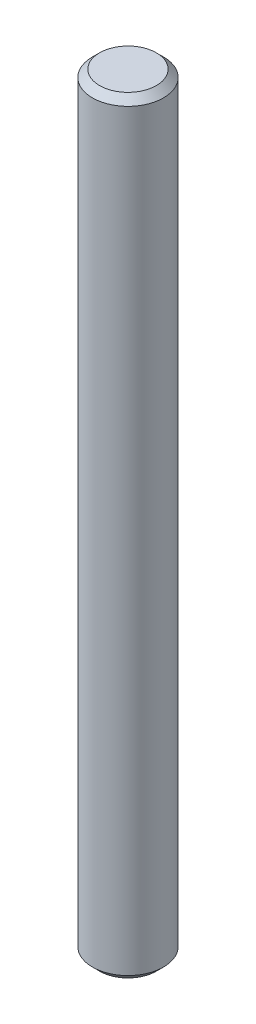
SolidWorks part; units mm, degrees
ref_plane "前视基准面" through (0, 0, 0) normal (0, 0, 1) x (1, 0, 0)
ref_plane "上视基准面" through (0, 0, 0) normal (0, 1, 0) x (1, 0, 0)
ref_plane "右视基准面" through (0, 0, 0) normal (1, 0, 0) x (0, 0, -1)
other "Configuration Table"
sketch "草图1" plane through (0, 0, 0) normal (0, 0, 1) x (1, 0, 0)
  line L0 (0, 17.9143) -> (0, -10.0949) construction
  line L1 (0, 54) -> (5, 54)
  line L2 (5, 54) -> (5, 15)
  line L4 (5, 15) -> (5, -15)
  line L6 (5, -15) -> (5, -54)
  line L7 (5, -54) -> (0, -54)
  line L8 (0, 0) -> (25.4592, 0) construction
  line L9 (0, 54) -> (0, -54)
  dimension "D1" = 5
  dimension "D3" = 30
  dimension "D4" = 39
  dimension "D5" = 39
revolve "旋转1" add sketch "草图1" angle 360 about L9
chamfer "倒角1" distance 1 angle 45 2 edges at (-5, -54, 0) (-5, 54, 0)
